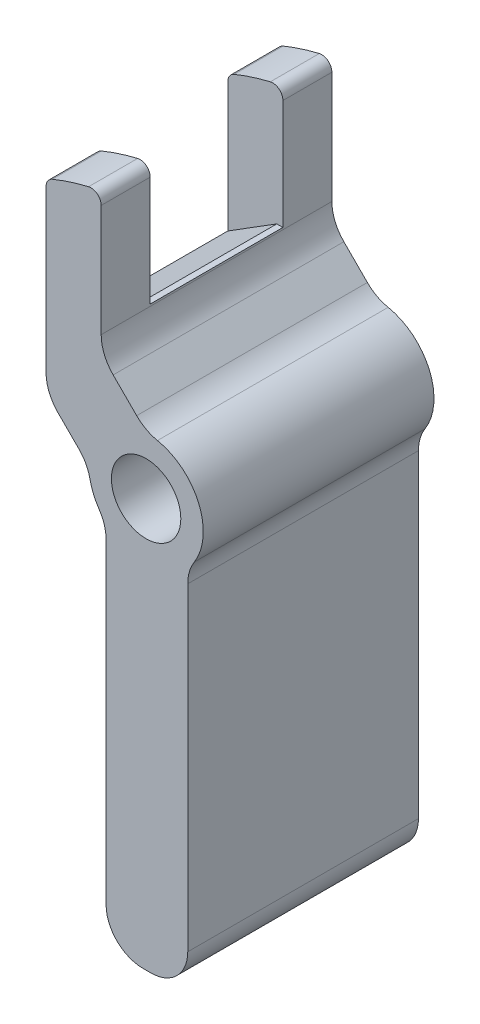
SolidWorks part; units mm, degrees
ref_plane "Front Plane" through (0, 0, 0) normal (0, 0, 1) x (1, 0, 0)
ref_plane "Top Plane" through (0, 0, 0) normal (0, 1, 0) x (1, 0, 0)
ref_plane "Right Plane" through (0, 0, 0) normal (1, 0, 0) x (0, 0, -1)
sketch "Sketch1" plane through (0, 0, 0) normal (0, 0, 1) x (1, 0, 0)
  line L0 (2.7401, 9.1947) -> (2.7401, -6.2921)
  line L1 (2.4997, 23.863) -> (2.4997, 17.7648)
  line L2 (4.6997, 11.9079) -> (-5.0848, 21.6924) construction
  line L3 (1.4093, 12.3699) -> (0.3855, 13.3937)
  line L4 (4.6997, 11.9079) -> (4.6997, -6.2346) construction
  line L5 (4.9401, -8.0921) -> (4.5401, -8.0921)
  line L6 (6.7401, -6.2921) -> (6.7401, 9.3166)
  line L8 (4.2377, 15.1983) -> (3.0855, 16.3506)
  line L10 (-0.2003, 14.8079) -> (-0.2003, 23.0324)
  arc A0 (2.4997, 23.863) -> (-0.2003, 23.0324) centre (4.6997, 11.9079) ccw
  arc A1 (7.0566, 10.3963) -> (5.2552, 14.6523) centre (4.6997, 11.9079) ccw
  circle A2 centre (4.6997, 11.9079) radius 1.7
  arc A3 (1.9553, 11.3524) -> (2.3899, 10.3252) centre (4.6997, 11.9079) ccw
  arc A4 (0.3855, 13.3937) -> (-0.2003, 14.8079) centre (1.7997, 14.8079) cw
  arc A5 (2.4997, 17.7648) -> (3.0855, 16.3506) centre (4.4997, 17.7648) ccw
  arc A6 (4.2377, 15.1983) -> (5.2552, 14.6523) centre (5.652, 16.6125) ccw
  arc A7 (1.4093, 12.3699) -> (1.9553, 11.3524) centre (-0.0049, 10.9557) cw
  arc A8 (6.7401, 9.3166) -> (7.0566, 10.3963) centre (8.7401, 9.3166) cw
  arc A9 (2.3899, 10.3252) -> (2.7401, 9.1947) centre (0.7401, 9.1947) cw
  arc A10 (6.7401, -6.2921) -> (4.9401, -8.0921) centre (4.9401, -6.2921) cw
  arc A11 (4.5401, -8.0921) -> (2.7401, -6.2921) centre (4.5401, -6.2921) cw
  point P22 (1.8998, 11.8794)
  point P27 (2.7401, 9.9079)
  point P30 (6.7401, -8.0921)
  point P33 (2.7401, -8.0921)
  dimension "D5" = 3.4
  dimension "D3" = 2.8
  dimension "D9" = 20
  dimension "D12" = 2
  dimension "D13" = 2
  dimension "D14" = 2
  dimension "D15" = 2
  dimension "D16" = 2
  dimension "D17" = 2
  dimension "D18" = 1.8
  dimension "D2" = 4.9
  dimension "D4" = 4
  dimension "D6" = 2
  dimension "D7" = 2
  dimension "D8" = 2.7
  dimension "D10" = 135
extrude "Boss-Extrude1" add sketch "Sketch1" along normal blind 11.3
sketch "Sketch2" plane through (2.4997, 0, 0) normal (1, 0, 0) x (0, 0, -1)
  line L1 (-8.9, 23.863) -> (-2.4, 23.863)
  line L2 (-8.9, 23.863) -> (-8.9, 17.863)
  line L3 (-8.9, 17.863) -> (-2.4, 17.863)
  line L4 (-2.4, 23.863) -> (-2.4, 17.863)
  line L5 (-5.65, -8.0921) -> (-5.65, 27.4134) construction
  line L6 (-11.3, -8.0921) -> (0, -8.0921) construction
  line L10 (-11.3, 23.863) -> (0, 23.863) construction
  dimension "D1" = 6.5
  dimension "D2" = 3.25
  dimension "D3" = 6
extrude "Cut-Extrude1" cut sketch "Sketch2" against normal up to next
chamfer "Chamfer1" distance 1.5 angle 58 1 edges at (-0.2003, 17.863, 5.65)
fillet "Fillet1" radius 0.5 4 edges at (2.4997, 23.863, 1.2) (2.4997, 23.863, 10.1) (-0.2003, 23.0324, 10.1) (-0.2003, 23.0324, 1.2)
